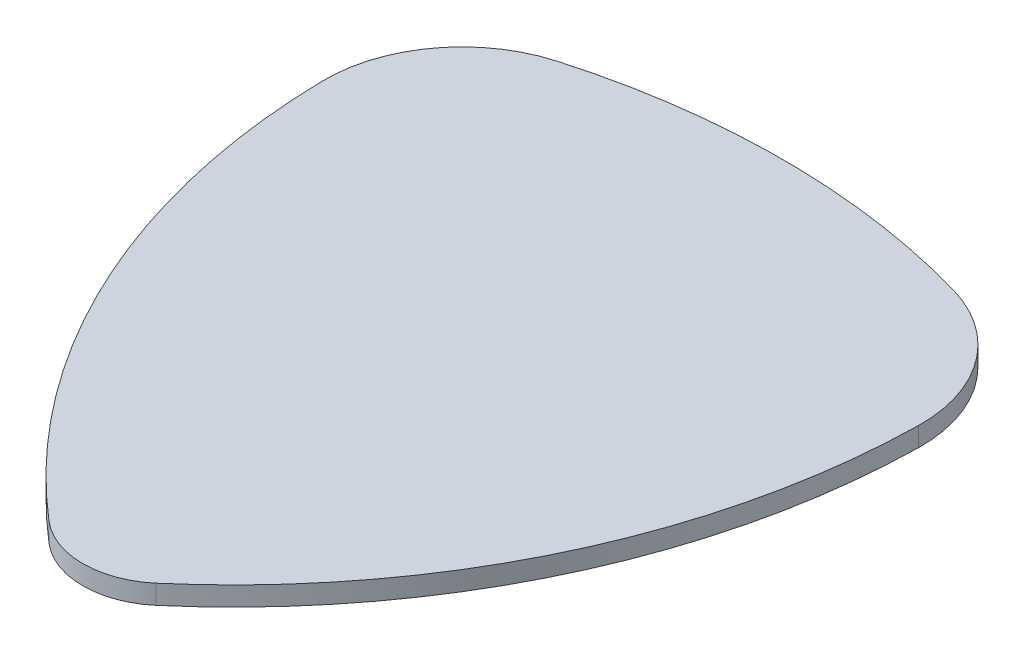
SolidWorks part; units mm, degrees
ref_plane "Front Plane" through (0, 0, 0) normal (0, 0, 1) x (1, 0, 0)
ref_plane "Top Plane" through (0, 0, 0) normal (0, 1, 0) x (1, 0, 0)
ref_plane "Right Plane" through (0, 0, 0) normal (1, 0, 0) x (0, 0, -1)
sketch "Sketch1" plane through (0, 0, 0) normal (0, 1, 0) x (1, 0, 0)
  line L0 (10.6517, -24) -> (10.6517, 4.3553) construction
  arc A0 (0, 0) -> (21.3033, 0) centre (10.6517, -24) cw
  arc A1 (0, 0) -> (10.6517, -24) centre (25.1658, -3.1946) ccw
  arc A2 (21.3033, 0) -> (10.6517, -24) centre (-3.8625, -3.1946) cw
  dimension "D1" = 25.3678
  dimension "D2" = 24
  dimension "D3" = 21.3033
extrude "Boss-Extrude1" add sketch "Sketch1" along normal blind 0.7
fillet "Fillet1" radius 5 1 edges at (21.3033, 0.35, 0)
fillet "Fillet2" radius 5 1 edges at (0, 0.35, 0)
fillet "Fillet3" radius 3 1 edges at (10.6517, 0.35, 24)
scale "Scale1" scale about centroid uniform scaling yes scale factor 1.2
sketch "草图1" plane through (0, 0.77, 0) normal (0, 1, 0) x (1, 0, 0)
  line L0 (10.6517, 4.4668) -> (10.6517, -26.0989) construction
  arc A0 (-2.3677, -2.6268) -> (8.3157, -25.2381) centre (28.0687, -2.0758) ccw construction
  arc A1 (12.9877, -25.2381) -> (23.671, -2.6268) centre (-6.7653, -2.0758) ccw construction
  arc A2 (8.3157, -25.2381) -> (12.9877, -25.2381) centre (10.6517, -22.4989) ccw construction
  arc A3 (19.3233, 3.2501) -> (1.9801, 3.2501) centre (10.6517, -27.0422) ccw construction
